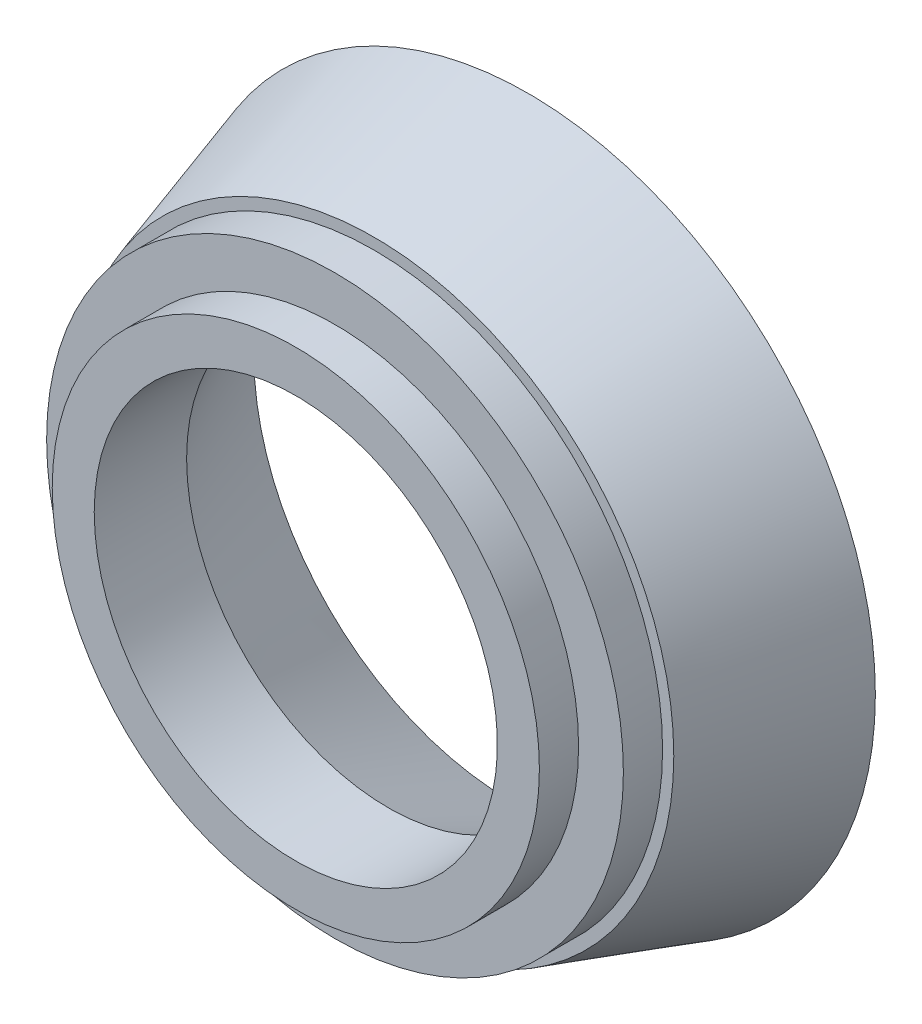
SolidWorks part; units mm, degrees
ref_plane "Ön Düzlem" through (0, 0, 0) normal (0, 0, 1) x (1, 0, 0)
ref_plane "Üst Düzlem" through (0, 0, 0) normal (0, 1, 0) x (1, 0, 0)
ref_plane "Sağ Düzlem" through (0, 0, 0) normal (1, 0, 0) x (0, 0, -1)
sketch "Sketch1" plane through (0, 0, 0) normal (0, 0, 1) x (1, 0, 0)
  circle A0 centre (0, 0) radius 62
ref_plane "Plane1" through (0, 0, 27.5) normal (0, 0, 1) x (1, 0, 0)
sketch "Sketch2" plane through (0, 0, 27.5) normal (0, 0, 1) x (1, 0, 0)
  circle A0 centre (0, 0) radius 53.5
loft "Loft1" add profiles "Sketch1", "Sketch2"
sketch "Sketch3" plane through (0, 0, 27.5) normal (0, 0, 1) x (1, 0, 0)
  circle A1 centre (0, 0) radius 51.5
extrude "Boss-Extrude1" add sketch "Sketch3" along normal blind 7
sketch "Sketch4" plane through (0, 0, 34.5) normal (0, 0, 1) x (1, 0, 0)
  circle A0 centre (0, 0) radius 43.5
extrude "Boss-Extrude2" add sketch "Sketch4" along normal blind 7
sketch "Sketch5" plane through (0, 0, 0) normal (0, 0, -1) x (-1, 0, 0)
  circle A0 centre (0, 0) radius 59.5
extrude "Cut-Extrude1" cut sketch "Sketch5" against normal blind 3
sketch "Sketch6" plane through (0, 0, 3) normal (0, 0, -1) x (-1, 0, 0)
  circle A0 centre (0, 0) radius 46
ref_plane "Plane2" through (0, 0, 25) normal (0, 0, -1) x (-1, 0, 0)
sketch "Sketch7" plane through (0, 0, 25) normal (0, 0, -1) x (-1, 0, 0)
  circle A0 centre (0, 0) radius 36
loft "Cut-Loft1" cut profiles "Sketch6", "Sketch7"
sketch "Sketch8" plane through (0, 0, 25) normal (0, 0, -1) x (-1, 0, 0)
  circle A1 centre (0, 0) radius 36
  circle A2 centre (0, 0) radius 36
  dimension "D1" = 0
extrude "Cut-Extrude2" cut sketch "Sketch8" against normal through all
